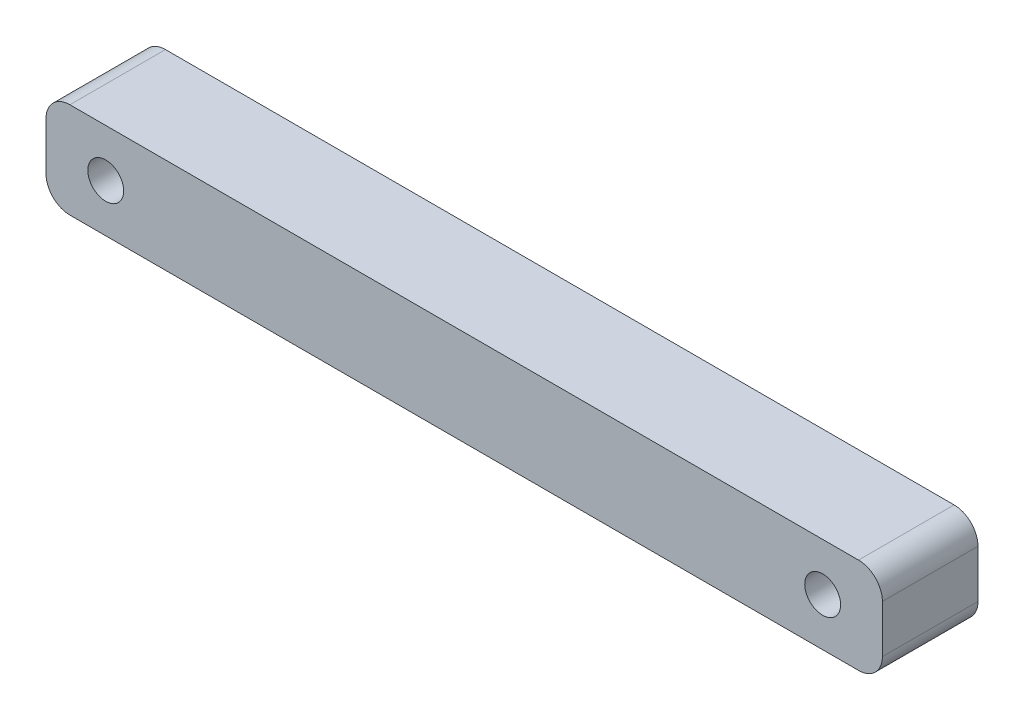
SolidWorks part; units mm, degrees
ref_plane "前视基准面" through (0, 0, 0) normal (0, 0, 1) x (1, 0, 0)
ref_plane "上视基准面" through (0, 0, 0) normal (0, 1, 0) x (1, 0, 0)
ref_plane "右视基准面" through (0, 0, 0) normal (1, 0, 0) x (0, 0, -1)
sketch "草图1" plane through (0, 0, 0) normal (0, 0, 1) x (1, 0, 0)
  line L0 (0, -4) -> (5, -4) construction
  line L1 (0, 0) -> (70, 0)
  line L2 (0, 0) -> (0, -8)
  line L3 (0, -8) -> (70, -8)
  line L4 (70, 0) -> (70, -8)
  line L5 (35, 0) -> (35, -65.1722) construction
  circle A0 centre (5, -4) radius 1.5
  circle A1 centre (65, -4) radius 1.5
  dimension "D3" = 3
  dimension "D1" = 8
  dimension "D2" = 5
extrude "凸台-拉伸1" add sketch "草图1" along normal blind 8
fillet "圆角1" radius 2 4 edges at (0, -8, 4) (0, 0, 4) (70, 0, 4) (70, -8, 4)
